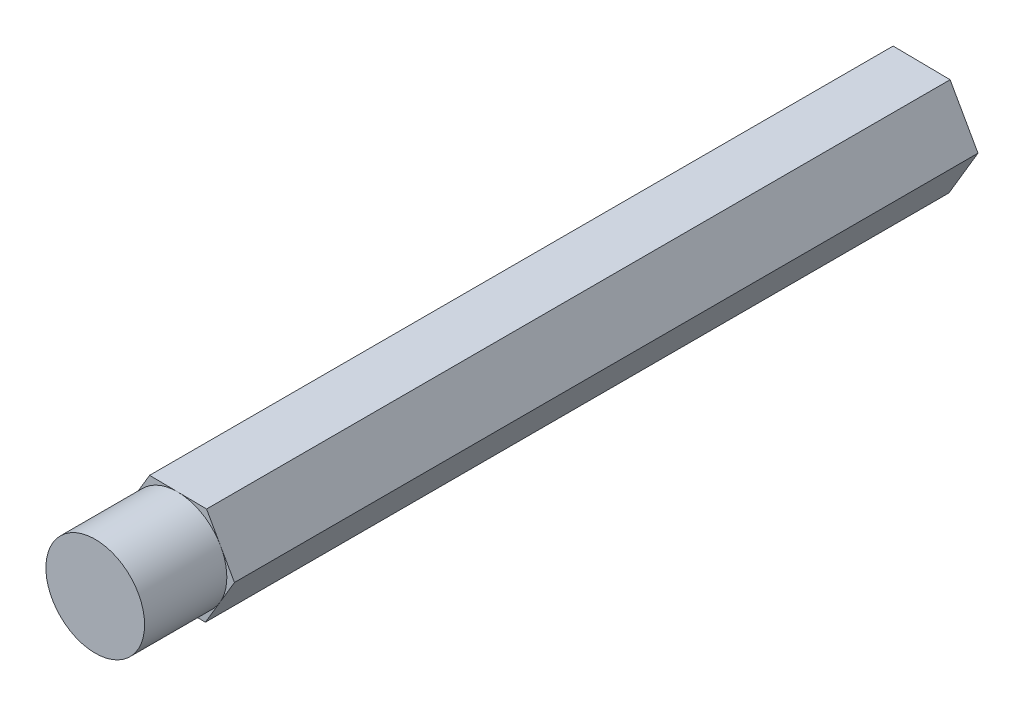
SolidWorks part; units mm, degrees
ref_plane "Front Plane" through (0, 0, 0) normal (0, 0, 1) x (1, 0, 0)
ref_plane "Top Plane" through (0, 0, 0) normal (0, 1, 0) x (1, 0, 0)
ref_plane "Right Plane" through (0, 0, 0) normal (1, 0, 0) x (0, 0, -1)
sketch "Sketch1" plane through (0, 0, 0) normal (0, 0, 1) x (1, 0, 0)
  line L1 (2.8069, 4.729) -> (-2.692, 4.7953)
  line L2 (-2.692, 4.7953) -> (-5.4989, 0.0663)
  line L3 (-5.4989, 0.0663) -> (-2.8069, -4.729)
  line L4 (-2.8069, -4.729) -> (2.692, -4.7953)
  line L5 (2.692, -4.7953) -> (5.4989, -0.0663)
  line L6 (5.4989, -0.0663) -> (2.8069, 4.729)
  circle A0 centre (0, 0) radius 4.7625 construction
  dimension "D1" = 9.525
extrude "Boss-Extrude1" add sketch "Sketch1" along normal blind 79.7052
sketch "Sketch5" plane through (0, 0, 79.7052) normal (0, 0, 1) x (1, 0, 0)
  circle A0 centre (0, 0) radius 4.7625
  circle A1 centre (0, 0) radius 5.4993
extrude "Cut-Extrude2" cut sketch "Sketch5" against normal blind 7.9375
